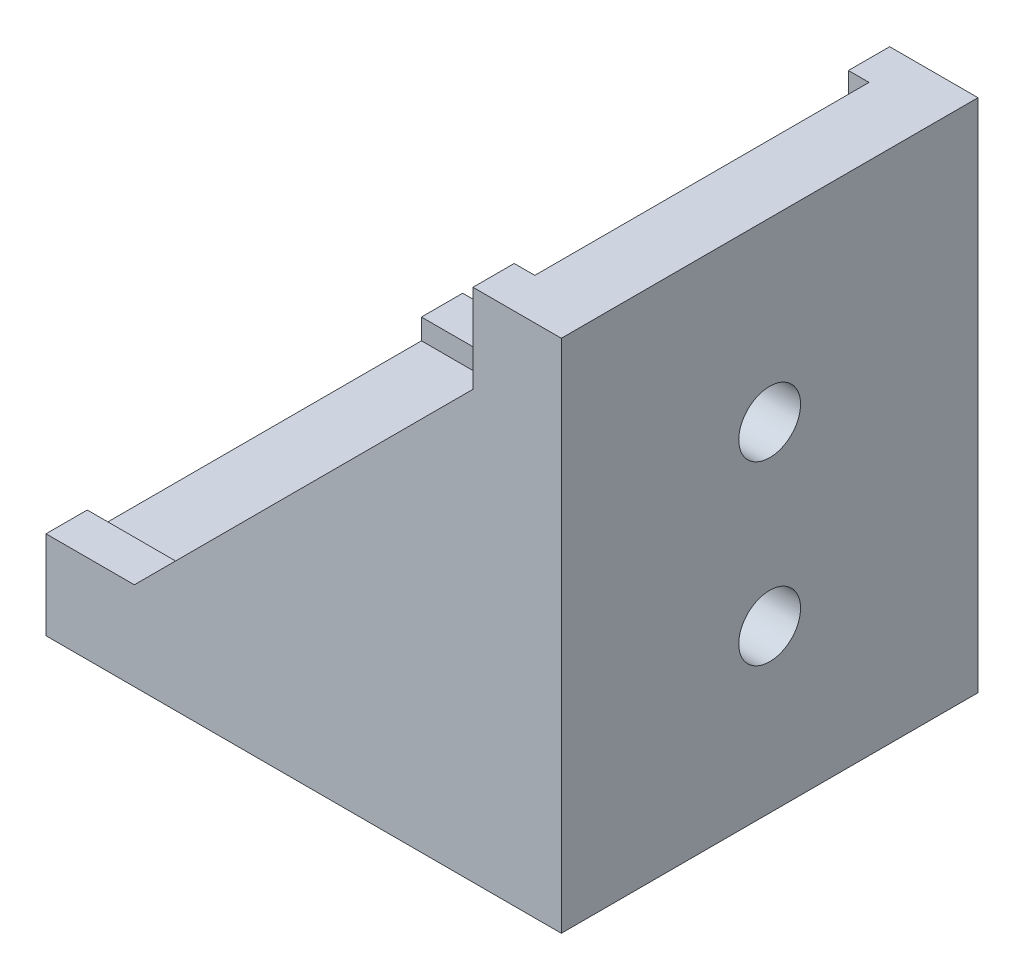
SolidWorks part; units mm, degrees
material "聚脂树脂"
ref_plane "前视基准面" through (0, 0, 0) normal (0, 0, 1) x (1, 0, 0)
ref_plane "上视基准面" through (0, 0, 0) normal (0, 1, 0) x (1, 0, 0)
ref_plane "右视基准面" through (0, 0, 0) normal (1, 0, 0) x (0, 0, -1)
other "Configuration Table"
sketch "草图1" plane through (0, 0, 0) normal (0, 0, 1) x (1, 0, 0)
  line L0 (0, 0) -> (35, 0)
  line L1 (35, 0) -> (35, 35)
  line L2 (35, 35) -> (29, 35)
  line L3 (29, 35) -> (29, 29)
  line L4 (29, 29) -> (6, 6)
  line L5 (6, 6) -> (0, 6)
  line L6 (0, 6) -> (0, 0)
  dimension "D1" = 35
  dimension "D2" = 6
  dimension "D3" = 6
extrude "凸台-拉伸1" add sketch "草图1" along normal mid plane 28.3
sketch "草图2" plane through (0, 0, 0) normal (0, 0, 1) x (1, 0, 0)
  line L0 (0, 4.6) -> (30.4, 4.6)
  line L1 (0, 6) -> (0, 0) construction
  line L2 (30.4, 4.6) -> (30.4, 35)
  line L3 (35, 35) -> (29, 35) construction
  line L4 (30.4, 35) -> (0, 35)
  line L5 (0, 35) -> (0, 4.6)
  line L6 (35, 0) -> (35, 35) construction
  dimension "D1" = 4.6
extrude "切除-拉伸1" cut sketch "草图2" along normal mid plane 22.7
sketch "草图4" plane through (0, 0, 0) normal (0, 1, 0) x (1, 0, 0)
  line L0 (-5.3812, 0) -> (45.3159, 0) construction
  line L3 (35, -14.15) -> (35, 14.15) construction
  circle A2 centre (20.85, 0) radius 2.55
  circle A3 centre (11, 0) radius 2.55
  dimension "D2" = 5.1
  dimension "D3" = 24
  dimension "D4" = 9.85
extrude "切除-拉伸2" cut sketch "草图4" along normal up to next
sketch "草图5" plane through (0, 0, 0) normal (1, 0, 0) x (0, 0, -1)
  line L0 (0, 44.9599) -> (0, -4.5954) construction
  line L4 (-14.15, 35) -> (14.15, 35) construction
  circle A2 centre (0, 23) radius 2.1
  circle A3 centre (0, 11) radius 2.1
  dimension "D2" = 4.2
  dimension "D3" = 12
  dimension "D4" = 12
extrude "切除-拉伸3" cut sketch "草图5" along normal up to next
